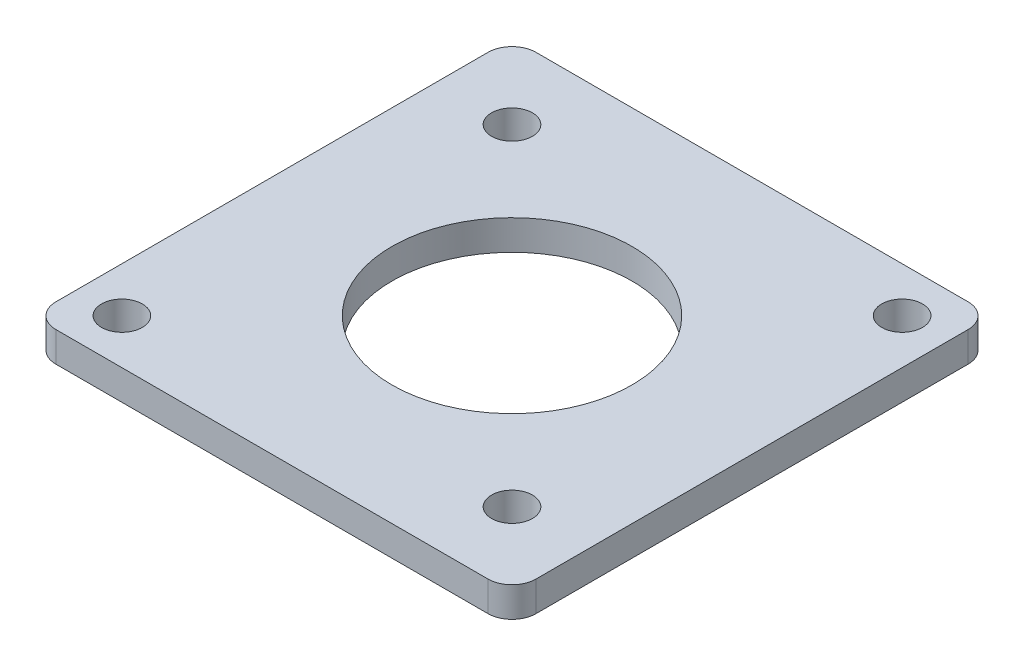
SolidWorks part; units mm, degrees
ref_plane "Front Plane" through (0, 0, 0) normal (0, 0, 1) x (1, 0, 0)
ref_plane "Top Plane" through (0, 0, 0) normal (0, 1, 0) x (1, 0, 0)
ref_plane "Right Plane" through (0, 0, 0) normal (1, 0, 0) x (0, 0, -1)
sketch "Sketch1" plane through (0, 0, 0) normal (0, 1, 0) x (1, 0, 0)
  line L0 (7.8885, -7.8885) -> (0, 0) construction
  line L1 (0, 0) -> (50.8, 0)
  line L2 (0, 0) -> (0, -50.8)
  line L3 (0, -50.8) -> (50.8, -50.8)
  line L4 (50.8, 0) -> (50.8, -50.8)
  line L5 (42.9115, -42.9115) -> (50.8, -50.8) construction
  circle A0 centre (25.4, -25.4) radius 12.7
  circle A1 centre (7.8885, -7.8885) radius 2.159
  circle A2 centre (42.9115, -42.9115) radius 2.159
  circle A3 centre (46.0375, -4.7625) radius 2.159
  circle A4 centre (4.7625, -46.0375) radius 2.159
  dimension "D5" = 25.4
  dimension "D6" = 4.318
  dimension "D7" = 4.318
  dimension "D11" = 4.318
  dimension "D12" = 4.318
  dimension "D1" = 50.8
  dimension "D2" = 50.8
  dimension "D3" = 25.4
  dimension "D4" = 25.4
  dimension "D8" = 49.53
  dimension "D9" = 45
  dimension "D10" = 45
  dimension "D13" = 4.7625
  dimension "D14" = 4.7625
  dimension "D15" = 4.7625
  dimension "D16" = 4.7625
extrude "Boss-Extrude1" add sketch "Sketch1" along normal blind 3.175
fillet "Fillet1" radius 2.54 4 edges at (50.8, 1.5875, 50.8) (0, 1.5875, 50.8) (50.8, 1.5875, 0) (0, 1.5875, 0)
